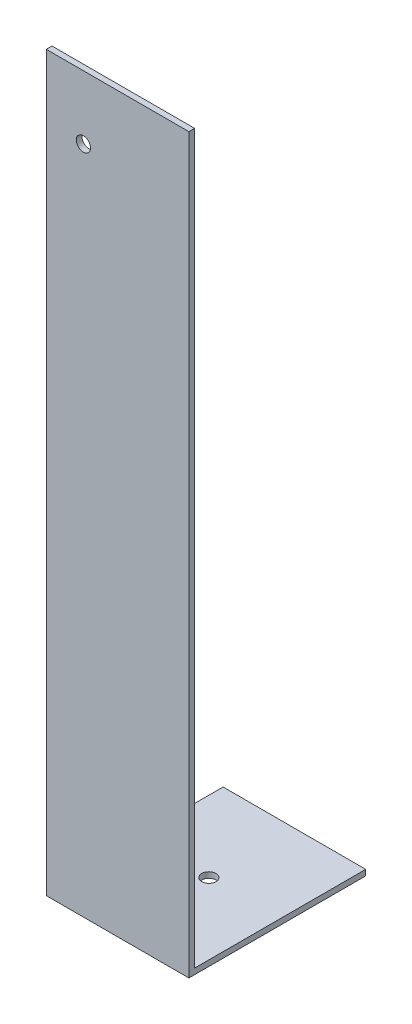
SolidWorks part; units mm, degrees
ref_plane "Alzado" through (0, 0, 0) normal (0, 0, 1) x (1, 0, 0)
ref_plane "Planta" through (0, 0, 0) normal (0, 1, 0) x (1, 0, 0)
ref_plane "Vista lateral" through (0, 0, 0) normal (1, 0, 0) x (0, 0, -1)
sketch "Croquis1" plane through (0, 0, 0) normal (1, 0, 0) x (0, 0, -1)
  line L0 (-20.2397, -215.0344) -> (-20.2397, 41.9656)
  line L1 (-20.2397, 41.9656) -> (-18.2397, 41.9656)
  line L2 (-18.2397, 41.9656) -> (-18.2397, -213.0344)
  line L3 (-18.2397, -213.0344) -> (41.7603, -213.0344)
  line L4 (41.7603, -213.0344) -> (41.7603, -215.0344)
  line L5 (41.7603, -215.0344) -> (-20.2397, -215.0344)
  dimension "D1" = 2
  dimension "D2" = 2
  dimension "D3" = 255
  dimension "D4" = 60
extrude "Saliente-Extruir1" add sketch "Croquis1" along normal blind 50
sketch "Croquis2" plane through (0, -213.0344, 0) normal (0, 1, 0) x (1, 0, 0)
  line L1 (50, 41.7603) -> (50, -18.2397) construction
  line L2 (50, -18.2397) -> (0, -18.2397) construction
  circle A0 centre (25, 11.7603) radius 2.5
  dimension "D1" = 5
  dimension "D2" = 25
  dimension "D3" = 30
extrude "Cortar-Extruir1" cut sketch "Croquis2" against normal blind 10
sketch "Croquis3" plane through (0, 0, 18.2397) normal (0, 0, -1) x (-1, 0, 0)
  circle A0 centre (-13.01, 19.7306) radius 2.5
  point P10 (-14.5612, 20.0569)
  point P11 (-13.3471, 19.7306)
  dimension "D1" = 5
extrude "Cortar-Extruir2" cut sketch "Croquis3" against normal blind 10
